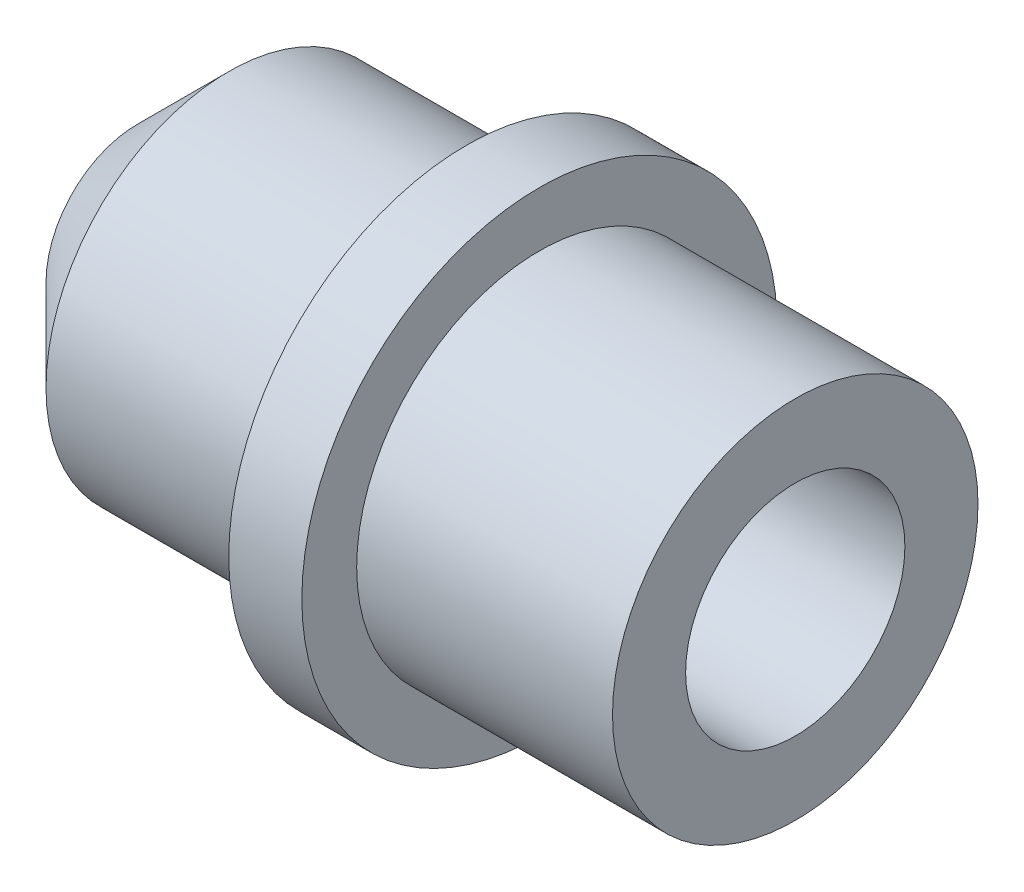
SolidWorks part; units mm, degrees
ref_plane "Спереди" through (0, 0, 0) normal (0, 0, 1) x (1, 0, 0)
ref_plane "Сверху" through (0, 0, 0) normal (0, 1, 0) x (1, 0, 0)
ref_plane "Справа" through (0, 0, 0) normal (1, 0, 0) x (0, 0, -1)
sketch "Эскиз1" plane through (0, 0, 0) normal (0, 1, 0) x (1, 0, 0)
  line L0 (-14.1176, 0) -> (17.5529, 0) construction
  line L1 (0.3726, -3) -> (0.3726, -5)
  line L2 (0.3726, -5) -> (-6.6274, -5)
  line L3 (-6.6274, -5) -> (-6.6274, -6.5)
  line L4 (-6.6274, -6.5) -> (-8.6274, -6.5)
  line L5 (-8.6274, -6.5) -> (-8.6274, -5)
  line L6 (-8.6274, -5) -> (-15.1274, -5)
  line L7 (-15.1274, -5) -> (-17.6274, -2.5)
  line L8 (-17.6274, -2.5) -> (-17.6274, -1.5)
  line L9 (-14.5366, -1.5) -> (-14.5366, -3)
  line L10 (-14.5366, -3) -> (0.3726, -3)
  line L11 (-14.5366, -1.5) -> (-17.6274, -1.5)
  dimension "D1" = 2
  dimension "D2" = 7
  dimension "D3" = 3
  dimension "D4" = 5
  dimension "D5" = 6.5
  dimension "D6" = 18
  dimension "D7" = 135
  dimension "D8" = 2.5
  dimension "D9" = 1.5
revolve "Повернуть1" add sketch "Эскиз1" angle 360 about L0
